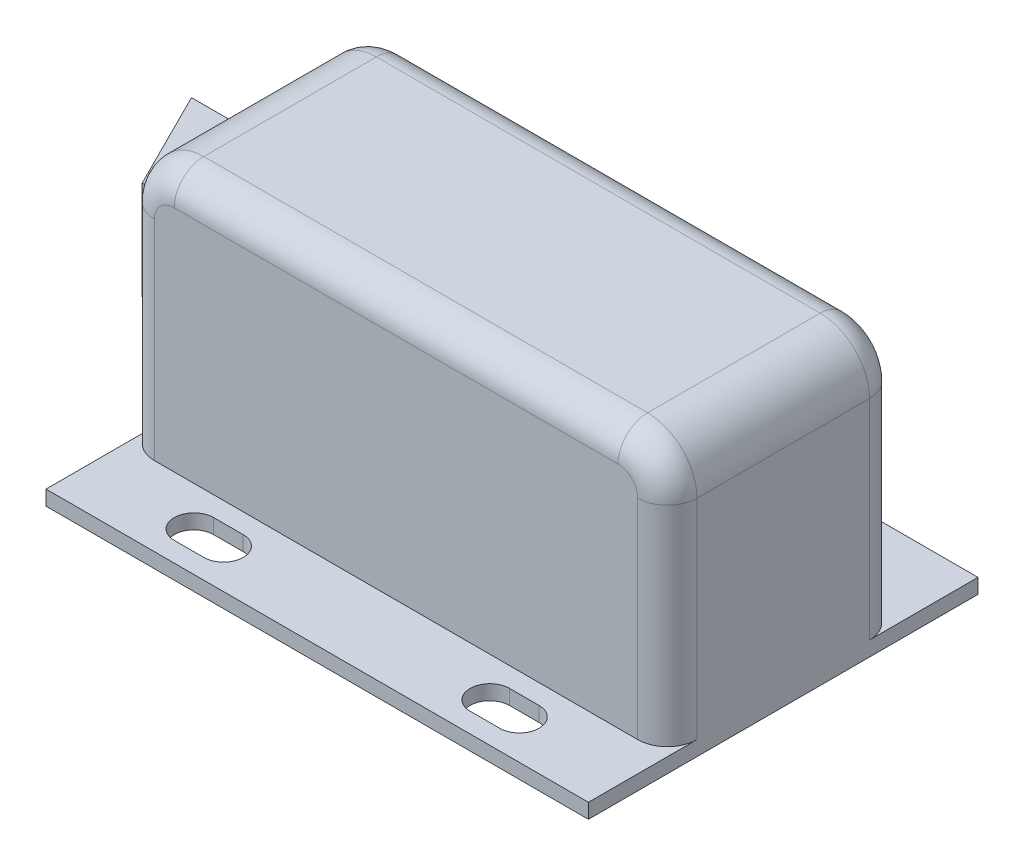
SolidWorks part; units mm, degrees
ref_plane "Front Plane" through (0, 0, 0) normal (0, 0, 1) x (1, 0, 0)
ref_plane "Top Plane" through (0, 0, 0) normal (0, 1, 0) x (1, 0, 0)
ref_plane "Right Plane" through (0, 0, 0) normal (1, 0, 0) x (0, 0, -1)
ref_plane "Plane1" through (0, 13.85, 0) normal (0, 1, 0) x (1, 0, 0)
sketch "Sketch1" plane through (0, 13.85, 0) normal (0, 1, 0) x (1, 0, 0)
  line L0 (-27.5, 8) -> (-27.5, -31.5)
  line L1 (-27.5, -31.5) -> (27.5, -31.5)
  line L2 (27.5, -31.5) -> (27.5, 8)
  line L3 (27.5, 8) -> (-27.5, 8)
extrude "Boss-Extrude1" add sketch "Sketch1" against normal blind 27.7
sketch "Sketch2" plane through (-27.5, 0, 0) normal (-1, 0, 0) x (0, 0, 1)
  line L0 (31.5, 13.85) -> (23.5, 13.85)
  line L1 (23.5, 13.85) -> (23.5, -12.35)
  line L2 (23.5, -12.35) -> (31.5, -12.35)
  line L3 (31.5, -12.35) -> (31.5, 13.85)
extrude "Cut-Extrude1" cut sketch "Sketch2" against normal through all
sketch "Sketch3" plane through (-27.5, 0, 0) normal (-1, 0, 0) x (0, 0, 1)
  line L0 (0, -12.35) -> (0, 13.85)
  line L1 (0, 13.85) -> (-8, 13.85)
  line L2 (-8, 13.85) -> (-8, -12.35)
  line L3 (-8, -12.35) -> (0, -12.35)
extrude "Cut-Extrude2" cut sketch "Sketch3" against normal through all
sketch "Sketch4" plane through (0, -12.35, 0) normal (0, 1, 0) x (-1, 0, 0)
  line L0 (-13.5, -2) -> (-16.5, -2)
  line L1 (-16.5, -6) -> (-13.5, -6)
  arc A0 (-16.5, -2) -> (-16.5, -6) centre (-16.5, -4) ccw
  arc A1 (-13.5, -6) -> (-13.5, -2) centre (-13.5, -4) ccw
extrude "Cut-Extrude3" cut sketch "Sketch4" against normal through all
sketch "Sketch5" plane through (0, -13.85, 0) normal (0, -1, 0) x (1, 0, 0)
  line L0 (-16.5, -6) -> (-13.5, -6)
  line L1 (-13.5, -2) -> (-16.5, -2)
  arc A0 (-13.5, -6) -> (-13.5, -2) centre (-13.5, -4) ccw
  arc A1 (-16.5, -2) -> (-16.5, -6) centre (-16.5, -4) ccw
extrude "Cut-Extrude4" cut sketch "Sketch5" against normal through all
sketch "Sketch6" plane through (0, -12.35, 0) normal (0, 1, 0) x (-1, 0, 0)
  line L0 (16.5, 29.5) -> (13.5, 29.5)
  line L1 (13.5, 25.5) -> (16.5, 25.5)
  arc A0 (13.5, 29.5) -> (13.5, 25.5) centre (13.5, 27.5) ccw
  arc A1 (16.5, 25.5) -> (16.5, 29.5) centre (16.5, 27.5) ccw
extrude "Cut-Extrude5" cut sketch "Sketch6" against normal through all
sketch "Sketch7" plane through (0, -13.85, 0) normal (0, -1, 0) x (1, 0, 0)
  line L0 (13.5, 25.5) -> (16.5, 25.5)
  line L1 (16.5, 29.5) -> (13.5, 29.5)
  arc A0 (16.5, 25.5) -> (16.5, 29.5) centre (16.5, 27.5) ccw
  arc A1 (13.5, 29.5) -> (13.5, 25.5) centre (13.5, 27.5) ccw
extrude "Cut-Extrude6" cut sketch "Sketch7" against normal through all
ref_plane "Plane2" through (0, -5.35, 0) normal (0, -1, 0) x (1, 0, 0)
sketch "Sketch8" plane through (0, -5.35, 0) normal (0, -1, 0) x (1, 0, 0)
  line L0 (-32.5, 16.75) -> (-37.5, 6.75)
  line L1 (-37.5, 6.75) -> (-27.5, 6.75)
  line L2 (-27.5, 6.75) -> (-27.5, 16.75)
  line L3 (-27.5, 16.75) -> (-32.5, 16.75)
extrude "Boss-Extrude2" add sketch "Sketch8" against normal blind 10
fillet "Fillet1" radius 5 2 edges at (27.5, 13.85, 11.75) (-27.5, 13.85, 11.75)
fillet "Fillet2" radius 3 10 edges at (27.5, -1.75, 23.5) (26.0355, 12.3855, 23.5) (0, 13.85, 23.5) (-26.0355, 12.3855, 23.5) (-27.5, -1.75, 23.5) (-27.5, -1.75, 0) (-26.0355, 12.3855, 0) (0, 13.85, 0) (26.0355, 12.3855, 0) (27.5, -1.75, 0)
